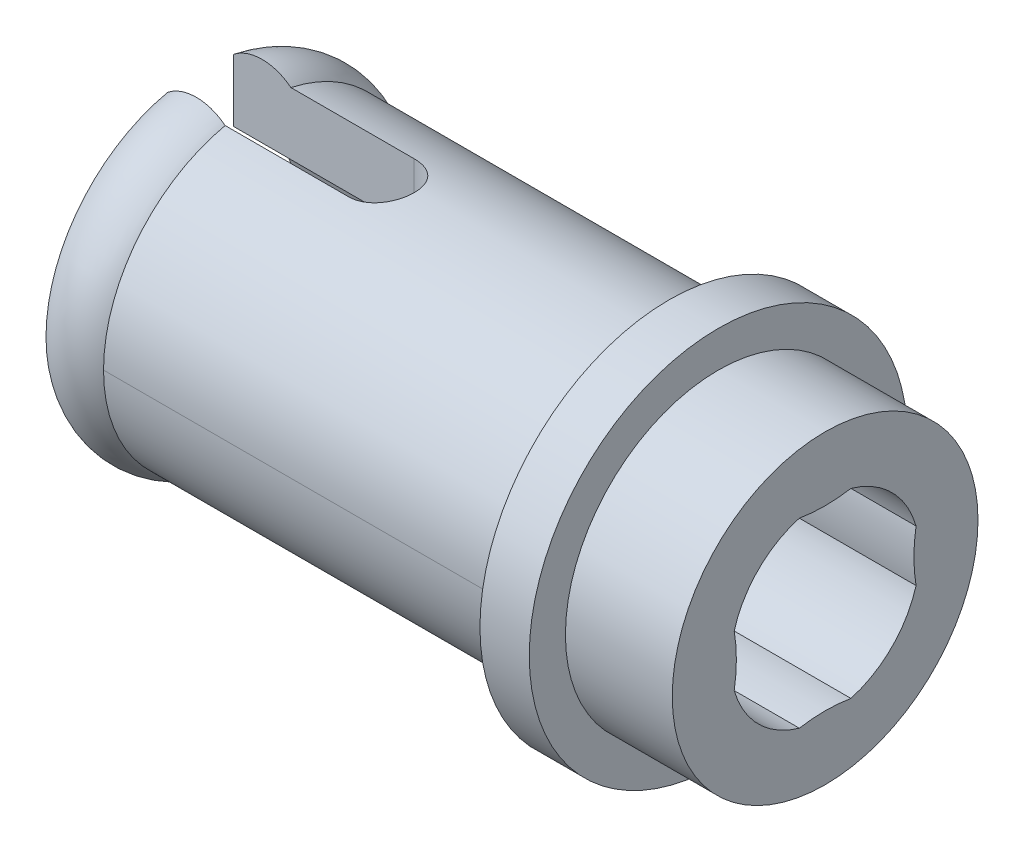
SolidWorks part; units mm, degrees
ref_plane "Front" through (0, 0, 0) normal (0, 0, 1) x (1, 0, 0)
ref_plane "Top" through (0, 0, 0) normal (0, 1, 0) x (1, 0, 0)
ref_plane "Right" through (0, 0, 0) normal (1, 0, 0) x (0, 0, -1)
sketch "Sketch1" plane through (0, 0, 0) normal (1, 0, 0) x (0, 0, -1)
  circle A0 centre (0, 0) radius 2.3622
  dimension "D1" = 4.7244
extrude "Base-Extrude" add sketch "Sketch1" along normal blind 1.651
sketch "Sketch3" plane through (0, 0, 0) normal (-1, 0, 0) x (0, 0, 1)
  circle A0 centre (0, 0) radius 2.921
  dimension "D1" = 5.842
extrude "Boss-Extrude1" add sketch "Sketch3" along normal blind 0.762
sketch "Sketch4" plane through (-0.762, 0, 0) normal (-1, 0, 0) x (0, 0, 1)
  circle A0 centre (0, 0) radius 2.3876
  dimension "D1" = 4.7752
extrude "Boss-Extrude2" add sketch "Sketch4" along normal blind 7.239
split line "Split Line1"
ref_plane "Plane1" through (-0.508, 0, 0) normal (1, 0, 0) x (0, 0, -1)
sketch "Sketch6" plane through (0, 0, 0) normal (0, 1, 0) x (1, 0, 0)
  line L0 (-0.762, 2.3876) -> (-8.001, 2.3876) construction
  line L1 (0, 0) -> (-8.8014, 0) construction
  line L2 (-8.001, 2.3876) -> (-7.112, 2.3876)
  arc A0 (-8.001, 2.3876) -> (-7.112, 2.3876) centre (-7.5565, 1.8156) cw
  dimension "D1" = 0.889
  dimension "D2" = 5.08
revolve "Boss-Revolve2" add sketch "Sketch6" angle 360 about L1
sketch "Sketch7" plane through (-8.001, 0, 0) normal (-1, 0, 0) x (0, 0, 1)
  circle A0 centre (0, 0) radius 1.4605
  dimension "D1" = 2.921
extrude "Cut-Extrude2" cut sketch "Sketch7" against normal through all
sketch "Sketch8" plane through (0, 0, 0) normal (0, 1, 0) x (1, 0, 0)
  line L0 (0, 0) -> (-8.8999, 0) construction
  line L1 (-8.001, 0.508) -> (-5.207, 0.508)
  line L3 (-5.207, -0.508) -> (-8.001, -0.508)
  line L4 (-8.001, -0.508) -> (-8.001, 0.508)
  line L5 (-8.001, -2.3876) -> (-8.001, 2.3876) construction
  arc A0 (-5.207, 0.508) -> (-5.207, -0.508) centre (-5.207, 0) cw
  dimension "D1" = 1.016
  dimension "D2" = 2.794
extrude "Cut-Extrude4" cut sketch "Sketch8" against normal through all and the other way through all
sketch "Sketch11" plane through (1.651, 0, 0) normal (1, 0, 0) x (0, 0, -1)
  line L0 (0, 0) -> (3.0369, 0) construction
  line L1 (0, 0) -> (0, 3.3772) construction
  circle A0 centre (0, 0) radius 1.4605 construction
  arc A1 (0.3985, 1.4051) -> (-0.3985, 1.4051) centre (0, 0) ccw
  arc A2 (0.3985, 1.4051) -> (-0.3985, 1.4051) centre (0, 3.7592) cw
  dimension "D1" = 4.7752
  dimension "D2" = 3.7592
extrude "Boss-Extrude11" add sketch "Sketch11" against normal blind 3.937
pattern_circular "CirPattern1" count 4 every 90 about axis through (0, 0, 0) along (1, 0, 0) of "Boss-Extrude11"
